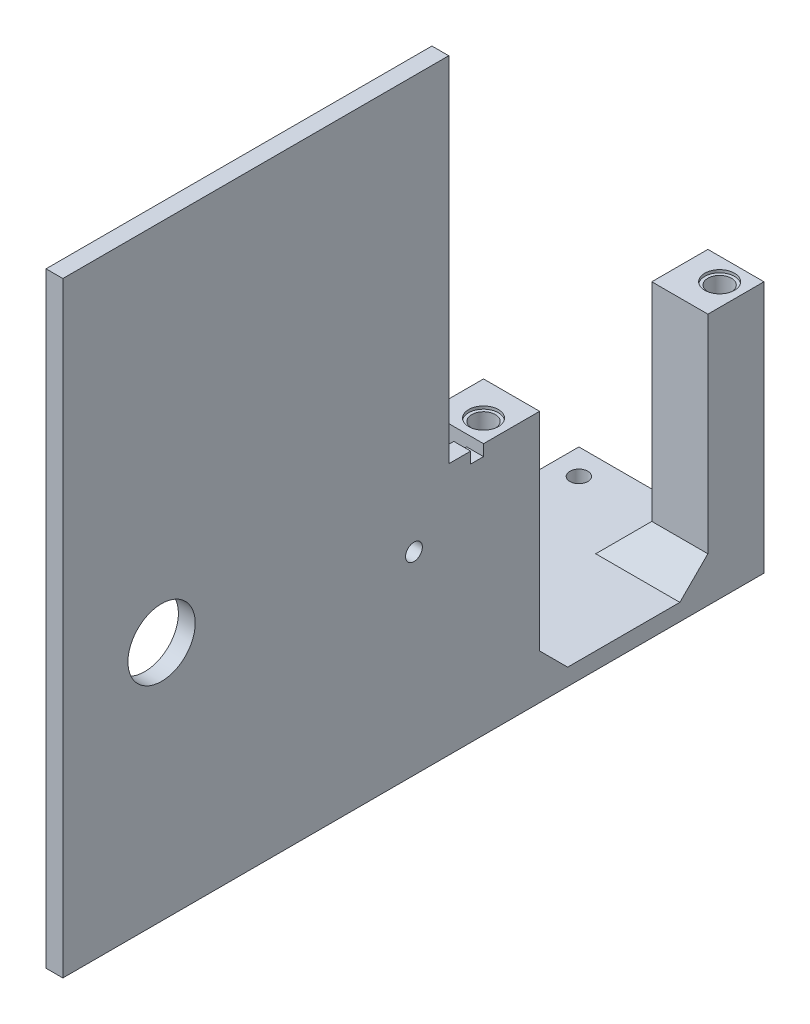
SolidWorks part; units mm, degrees
ref_plane "Front Plane" through (0, 0, 0) normal (0, 0, 1) x (1, 0, 0)
ref_plane "Top Plane" through (0, 0, 0) normal (0, 1, 0) x (1, 0, 0)
ref_plane "Right Plane" through (0, 0, 0) normal (1, 0, 0) x (0, 0, -1)
sketch "Sketch1" plane through (0, 0, 0) normal (0, 1, 0) x (1, 0, 0)
  line L1 (-6.5124, 9.686) -> (1.4876, 9.686)
  line L2 (-6.5124, 9.686) -> (-6.5124, -40.314)
  line L3 (-6.5124, -40.314) -> (1.4876, -40.314)
  line L4 (1.4876, 9.686) -> (1.4876, -40.314)
  line L5 (1.4876, 9.686) -> (26.4876, 9.686)
  line L6 (1.4876, 9.686) -> (1.4876, -40.314)
  line L7 (1.4876, -40.314) -> (26.4876, -40.314)
  line L8 (26.4876, 9.686) -> (26.4876, -40.314)
  circle A0 centre (-1.9624, -35.764) radius 1.6
  circle A1 centre (-1.9624, 5.136) radius 1.6
  dimension "D4" = 3.2
  dimension "D5" = 3.2
  dimension "D6" = 4.55
  dimension "D7" = 4.55
  dimension "D8" = 4.55
  dimension "D9" = 4.55
  dimension "D1" = 8
  dimension "D2" = 50
  dimension "D3" = 25
extrude "Boss-Extrude1" add sketch "Sketch1" along normal blind 3 contours A1 | A0 | L5 L8 L7 L3 L2 L1
sketch "Sketch2" plane through (0, 3, 0) normal (0, 1, 0) x (1, 0, 0)
  line L1 (26.4876, -40.314) -> (16.4876, -40.314)
  line L2 (26.4876, -40.314) -> (26.4876, -30.314)
  line L3 (26.4876, -30.314) -> (16.4876, -30.314)
  line L4 (16.4876, -40.314) -> (16.4876, -30.314)
  line L5 (26.4876, 9.686) -> (16.4876, 9.686)
  line L6 (26.4876, 9.686) -> (26.4876, -0.314)
  line L7 (26.4876, -0.314) -> (16.4876, -0.314)
  line L8 (16.4876, 9.686) -> (16.4876, -0.314)
  dimension "D1" = 10
  dimension "D2" = 10
  dimension "D3" = 10
  dimension "D4" = 10
extrude "Boss-Extrude2" add sketch "Sketch2" along normal blind 42
chamfer "Chamfer1" distance 5 angle 45 4 edges at (16.4876, 3, -4.686) (21.4876, 3, 0.314) (16.4876, 3, 35.314) (21.4876, 3, 30.314)
ref_plane "Plane1" through (0, 45, 0) normal (0, 1, 0) x (1, 0, 0)
sketch "Sketch3" plane through (0, 45, 0) normal (0, 1, 0) x (1, 0, 0)
  line L0 (26.4876, -40.314) -> (26.4876, -30.314) construction
  line L1 (16.4876, -40.314) -> (26.4876, -40.314) construction
  line L2 (26.4876, -0.314) -> (26.4876, 9.686) construction
  line L3 (26.4876, 9.686) -> (16.4876, 9.686) construction
  circle A0 centre (22.5376, -36.364) radius 2.1
  circle A1 centre (22.5376, 5.736) radius 2.1
  dimension "D1" = 4.2
  dimension "D3" = 3.95
  dimension "D4" = 4.2
  dimension "D6" = 3.95
  dimension "D2" = 3.95
  dimension "D5" = 3.95
extrude "Cut-Extrude1" cut sketch "Sketch3" against normal blind 52
sketch "Sketch4" plane through (0, 45, 0) normal (0, 1, 0) x (1, 0, 0)
  circle A0 centre (22.5376, -36.364) radius 2.65
  circle A1 centre (22.5376, 5.736) radius 2.65
  dimension "D1" = 5.3
  dimension "D2" = 5.3
extrude "Cut-Extrude2" cut sketch "Sketch4" against normal blind 0.5
ref_plane "Plane2" through (0, 22.5, 0) normal (0, -1, 0) x (-1, 0, 0)
mirror "Mirror1" about plane through (0, 22.5, 0) normal (0, -1, 0) of "Cut-Extrude2"
sketch "Sketch5" plane through (0, 0, 40.314) normal (0, 0, 1) x (1, 0, 0)
  line L0 (26.4876, 45) -> (26.4876, 0) construction
  line L1 (26.4876, 43) -> (23.4876, 43)
  line L2 (26.4876, 43) -> (26.4876, 0)
  line L3 (26.4876, 0) -> (23.4876, 0)
  line L4 (23.4876, 43) -> (23.4876, 0)
  line L5 (-6.5124, 0) -> (26.4876, 0) construction
  line L6 (16.4876, 45) -> (26.4876, 45) construction
  dimension "D1" = 3
  dimension "D2" = 2
extrude "Boss-Extrude3" add sketch "Sketch5" along normal blind 75
sketch "Sketch6" plane through (0, 43, 0) normal (0, 1, 0) x (1, 0, 0)
  line L0 (23.4876, -115.314) -> (23.4876, -40.314) construction
  line L1 (23.4876, -42.614) -> (26.4876, -42.614)
  line L2 (23.4876, -42.614) -> (23.4876, -46.514)
  line L3 (23.4876, -46.514) -> (26.4876, -46.514)
  line L4 (26.4876, -42.614) -> (26.4876, -46.514)
  line L5 (26.4876, -115.314) -> (26.4876, -40.314) construction
  line L6 (16.4876, -40.314) -> (26.4876, -40.314) construction
  dimension "D1" = 2.3
  dimension "D2" = 3.9
extrude "Boss-Extrude4" add sketch "Sketch6" along normal up to surface (2 mm away) up to face at (22.5376, 45, 39.014)
sketch "Sketch7" plane through (0, 43, 0) normal (0, 1, 0) x (1, 0, 0)
  line L1 (23.4876, -115.314) -> (26.4876, -115.314)
  line L2 (23.4876, -115.314) -> (23.4876, -46.514)
  line L3 (23.4876, -46.514) -> (26.4876, -46.514)
  line L4 (26.4876, -115.314) -> (26.4876, -46.514)
extrude "Boss-Extrude5" add sketch "Sketch7" along normal blind 5
sketch "Sketch8" plane through (23.4876, 0, 0) normal (-1, 0, 0) x (0, 0, 1)
  circle A0 centre (52.714, 34.5) radius 1.5
  dimension "D1" = 3
extrude "Cut-Extrude3" cut sketch "Sketch8" against normal blind 5
sketch "Sketch9" plane through (0, 48, 0) normal (0, 1, 0) x (1, 0, 0)
  line L1 (23.4876, -46.514) -> (26.4876, -46.514)
  line L2 (23.4876, -46.514) -> (23.4876, -115.314)
  line L3 (23.4876, -115.314) -> (26.4876, -115.314)
  line L4 (26.4876, -46.514) -> (26.4876, -115.314)
extrude "Boss-Extrude6" add sketch "Sketch9" along normal blind 15
sketch "Sketch10" plane through (23.4876, 0, 0) normal (-1, 0, 0) x (0, 0, 1)
  line L0 (52.714, 34.5) -> (82.714, 34.5) construction
  line L1 (82.714, 34.5) -> (97.714, 34.5) construction
  line L2 (97.714, 34.5) -> (97.714, 43) construction
  line L3 (97.714, 28) -> (97.714, 0) construction
  line L4 (115.314, 0) -> (40.314, 0) construction
  line L5 (97.714, 43) -> (97.714, 28) construction
  circle A0 centre (97.714, 43) radius 6
  dimension "D1" = 28
  dimension "D5" = 12
  dimension "D2" = 30
  dimension "D3" = 15
  dimension "D4" = 15
extrude "Cut-Extrude4" cut sketch "Sketch10" against normal blind 10
sketch "Sketch11" plane through (0, 63, 0) normal (0, 1, 0) x (1, 0, 0)
  line L1 (26.4876, -46.514) -> (23.4876, -46.514)
  line L2 (26.4876, -46.514) -> (26.4876, -115.314)
  line L3 (26.4876, -115.314) -> (23.4876, -115.314)
  line L4 (23.4876, -46.514) -> (23.4876, -115.314)
extrude "Boss-Extrude7" add sketch "Sketch11" along normal blind 45
